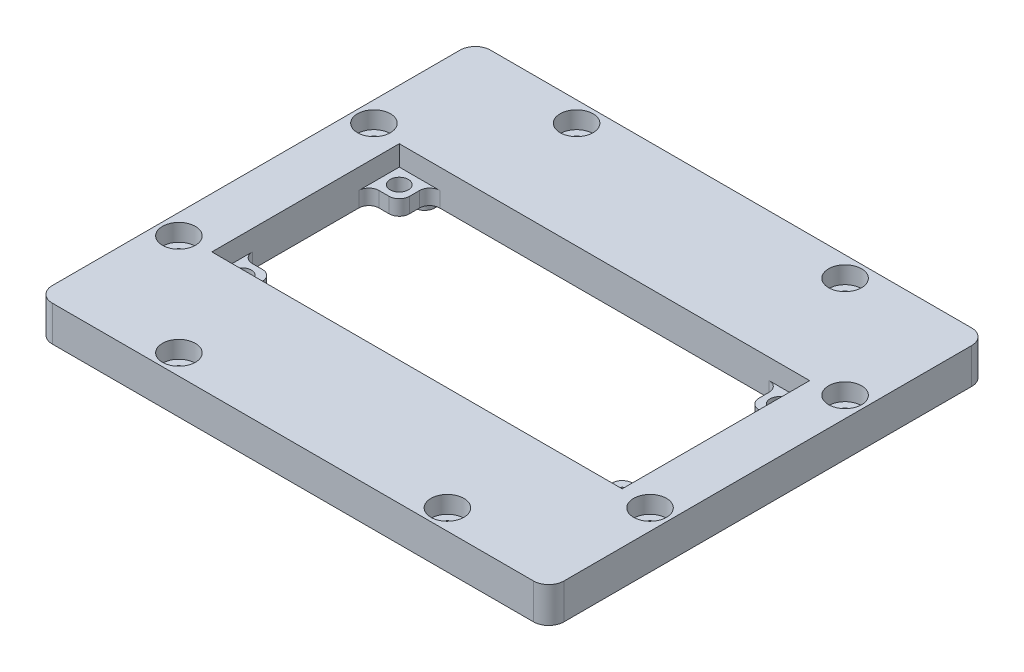
SolidWorks part; units mm, degrees
ref_plane "Front Plane" through (0, 0, 0) normal (0, 0, 1) x (1, 0, 0)
ref_plane "Top Plane" through (0, 0, 0) normal (0, 1, 0) x (1, 0, 0)
ref_plane "Right Plane" through (0, 0, 0) normal (1, 0, 0) x (0, 0, -1)
sketch "Sketch1" plane through (0, 0, 0) normal (0, 1, 0) x (1, 0, 0)
  line L1 (-50.5, -43.25) -> (50.5, -43.25)
  line L2 (-50.5, -43.25) -> (-50.5, 43.25)
  line L3 (-50.5, 43.25) -> (50.5, 43.25)
  line L4 (50.5, -43.25) -> (50.5, 43.25)
  line L5 (-50.5, -43.25) -> (50.5, 43.25) construction
  line L6 (-50.5, 43.25) -> (50.5, -43.25) construction
  point P0 (0, 0)
  dimension "D1" = 86.5
  dimension "D2" = 101
extrude "Boss-Extrude1" add sketch "Sketch1" along normal blind 7
sketch "Sketch2" plane through (0, 7, 0) normal (0, 1, 0) x (1, 0, 0)
  line L0 (50.5, -43.25) -> (50.5, 43.25) construction
  line L5 (-46.5, 39.25) -> (46.5, 39.25) construction
  line L6 (-46.5, 39.25) -> (-46.5, -39.25) construction
  line L11 (-46.5, -39.25) -> (46.5, -39.25) construction
  line L12 (46.5, 39.25) -> (46.5, -39.25) construction
  line L13 (0, -39.25) -> (0, 39.25) construction
  line L14 (-46.5, 0) -> (46.5, 0) construction
  line L15 (50.5, 43.25) -> (-50.5, 43.25) construction
  circle A0 centre (26.5, 39.25) radius 1
  circle A1 centre (46.5, 19.25) radius 1
  circle A2 centre (46.5, -19.25) radius 1
  circle A3 centre (26.5, -39.25) radius 1
  circle A4 centre (-26.5, -39.25) radius 1
  circle A5 centre (-46.5, -19.25) radius 1
  circle A6 centre (-46.5, 19.25) radius 1
  circle A7 centre (-26.5, 39.25) radius 1
  point P0 (0, 0)
  dimension "D1" = 2
  dimension "D2" = 20
  dimension "D3" = 20
  dimension "D4" = 4
  dimension "D5" = 4
hole_wizard "CBORE for M3 Hex Socket Head Cap Screw1" positions "Sketch5" profile "Sketch7" counterbore size "M3" standard "ISO" end condition through all
sketch "Sketch5" plane through (0, 7, 0) normal (0, 1, 0) x (1, 0, 0)
  point P19 (26.5, 39.25)
  point P22 (46.5, 19.25)
  point P25 (46.5, -19.25)
  point P28 (26.5, -39.25)
  point P31 (-26.5, -39.25)
  point P34 (-46.5, -19.25)
  point P37 (-46.5, 19.25)
  point P40 (-26.5, 39.25)
sketch "Sketch7" plane through (26.5, 7, -39.25) normal (1, 0, 0) x (0, 0, 1)
  line L0 (0, 0) -> (0, 7)
  line L1 (0, 7) -> (1.7, 7)
  line L3 (1.7, 7) -> (1.7, 3.4)
  line L4 (1.7, 3.4) -> (3.25, 3.4)
  line L5 (3.25, 3.4) -> (3.25, 0)
  line L7 (3.25, 0) -> (0, 0)
  line L11 (0, -6.35) -> (0, 107.95) construction
  dimension "Thru Hole Dia." = 3.4
  dimension "Thru Hole Depth" = 7
  dimension "C'Bore Dia." = 6.5
  dimension "C'Bore Depth" = 3.4
sketch "Sketch8" plane through (0, 0, 0) normal (0, -1, 0) x (1, 0, 0)
  line L0 (42, -34.75) -> (-42, -34.75) construction
  line L1 (42, -34.75) -> (27, -34.75)
  line L2 (27, -34.75) -> (27, -29.75)
  line L3 (27, -29.75) -> (37, -29.75)
  line L4 (37, -29.75) -> (37, -19.75)
  line L5 (37, -19.75) -> (42, -19.75)
  line L6 (42, -19.75) -> (42, -34.75)
  line L7 (-42, -19.75) -> (-42, -34.75)
  line L8 (-42, 34.75) -> (-27, 34.75)
  line L9 (-27, 34.75) -> (-27, 29.75)
  line L10 (-27, 29.75) -> (-37, 29.75)
  line L11 (-37, 29.75) -> (-37, 19.75)
  line L12 (42, -34.75) -> (42, 34.75)
  line L13 (42, 34.75) -> (-42, 34.75)
  line L14 (-42, 34.75) -> (-42, -34.75)
  line L15 (-42, -34.75) -> (42, -34.75)
  line L16 (42, -34.75) -> (42, 34.75) construction
  line L17 (42, 34.75) -> (-42, 34.75) construction
  line L18 (-42, 34.75) -> (-42, -34.75) construction
  line L19 (-42, -34.75) -> (42, -34.75) construction
  line L20 (-37, 19.75) -> (-42, 19.75)
  line L21 (-42, 19.75) -> (-42, 34.75)
  line L22 (0, 10.1371) -> (0, 0) construction
  line L23 (0, 0) -> (11.6132, 0) construction
  line L24 (42, 19.75) -> (42, 34.75)
  line L25 (37, 19.75) -> (42, 19.75)
  line L26 (37, 29.75) -> (37, 19.75)
  line L27 (27, 29.75) -> (37, 29.75)
  line L28 (27, 34.75) -> (27, 29.75)
  line L29 (42, 34.75) -> (27, 34.75)
  line L30 (-37, -19.75) -> (-42, -19.75)
  line L31 (-37, -29.75) -> (-37, -19.75)
  line L32 (-27, -29.75) -> (-37, -29.75)
  line L33 (-27, -34.75) -> (-27, -29.75)
  line L34 (-42, -34.75) -> (-27, -34.75)
  dimension "D2" = 15
  dimension "D3" = 10
  dimension "D1" = 8.5
extrude "Boss-Extrude2" add sketch "Sketch8" along normal blind 4
fillet "Fillet1" radius 2 24 edges at (-27, -2, -29.75) (-37, -2, -29.75) (-37, -2, -19.75) (-42, -2, -19.75) (-42, -2, -34.75) (-27, -2, -34.75) (27, -2, 29.75) (37, -2, 29.75) (37, -2, 19.75) (42, -2, 19.75) (42, -2, 34.75) (27, -2, 34.75) (37, -2, -19.75) (37, -2, -29.75) (27, -2, -29.75) (27, -2, -34.75) (42, -2, -34.75) (42, -2, -19.75) (-27, -2, 29.75) (-27, -2, 34.75) (-42, -2, 34.75) (-37, -2, 19.75) (-37, -2, 29.75) (-42, -2, 19.75)
fillet "Fillet2" radius 3 4 edges at (50.5, 3.5, 43.25) (-50.5, 3.5, 43.25) (50.5, 3.5, -43.25) (-50.5, 3.5, -43.25)
sketch "Sketch11" plane through (0, 7, 0) normal (0, 1, 0) x (1, 0, 0)
  line L0 (47.5, 43.25) -> (-47.5, 43.25) construction
  line L1 (-40.5, 18.25) -> (40.5, 18.25)
  line L2 (-40.5, 18.25) -> (-40.5, -18.75)
  line L3 (-40.5, -18.75) -> (40.5, -18.75)
  line L4 (40.5, 18.25) -> (40.5, -18.75)
  line L5 (0, -18.75) -> (0, 18.25) construction
  line L6 (-40.5, -0.25) -> (40.5, -0.25) construction
  circle A1 centre (-37.5, 15.25) radius 1.8 construction
  circle A2 centre (37.5, 15.25) radius 1.8 construction
  circle A3 centre (37.5, -15.75) radius 1.8 construction
  circle A4 centre (-37.5, -15.75) radius 1.8 construction
  point P0 (0, -0.25)
  dimension "D4" = 75
  dimension "D5" = 31
  dimension "D6" = 3.6
  dimension "D1" = 25
  dimension "D2" = 81
  dimension "D3" = 37
extrude "Cut-Extrude2" cut sketch "Sketch11" against normal through all and the other way through all
sketch "Sketch16" plane through (0, 7, 0) normal (0, 1, 0) x (1, 0, 0)
  line L0 (-32.5, -24.25) -> (-12.5, -24.25) construction
  line L1 (-32.5, -22.75) -> (-12.5, -22.75)
  line L2 (-32.5, -25.75) -> (-12.5, -25.75)
  line L3 (40.5, -18.75) -> (-40.5, -18.75) construction
  line L4 (-40.5, -18.75) -> (-40.5, 18.25) construction
  arc A0 (-32.5, -22.75) -> (-32.5, -25.75) centre (-32.5, -24.25) ccw
  arc A1 (-12.5, -25.75) -> (-12.5, -22.75) centre (-12.5, -24.25) ccw
  point P2 (-22.5, -24.25)
  dimension "D1" = 20
  dimension "D2" = 3
  dimension "D3" = 4
  dimension "D4" = 8
sketch "Sketch13" plane through (0, 0, 0) normal (0, -1, 0) x (1, 0, 0)
  line L0 (0, 18.75) -> (0, -18.25) construction
  line L1 (-40.5, 0.25) -> (40.5, 0.25) construction
  line L2 (0, 18.75) -> (0, -18.25) construction
  line L3 (-40.5, 0.25) -> (40.5, 0.25) construction
  line L4 (-34.5, 18.75) -> (-34.5, 12.75)
  line L5 (-40.5, -18.25) -> (-34.5, -18.25)
  line L6 (-40.5, -18.25) -> (-40.5, -12.25)
  line L7 (-40.5, -12.25) -> (-34.5, -12.25)
  line L8 (-34.5, -18.25) -> (-34.5, -12.25)
  line L9 (-40.5, 12.75) -> (-34.5, 12.75)
  line L10 (-40.5, 18.75) -> (-40.5, 12.75)
  line L11 (-40.5, 18.75) -> (-34.5, 18.75)
  line L12 (40.5, 18.75) -> (34.5, 18.75)
  line L13 (40.5, 18.75) -> (40.5, 12.75)
  line L14 (40.5, 12.75) -> (34.5, 12.75)
  line L15 (34.5, 18.75) -> (34.5, 12.75)
  line L16 (34.5, -18.25) -> (34.5, -12.25)
  line L17 (40.5, -12.25) -> (34.5, -12.25)
  line L18 (40.5, -18.25) -> (40.5, -12.25)
  line L19 (40.5, -18.25) -> (34.5, -18.25)
  circle A0 centre (-37.5, -15.25) radius 1.8 construction
  circle A1 centre (-37.5, -15.25) radius 1.8
  circle A2 centre (-37.5, 15.75) radius 1.8
  circle A3 centre (37.5, 15.75) radius 1.8
  circle A4 centre (37.5, -15.25) radius 1.8
  dimension "D1" = 3
extrude "Boss-Extrude3" add sketch "Sketch13" against normal blind 3
fillet "Fillet3" radius 2 12 edges at (34.5, 1.5, -12.25) (34.5, 1.5, 12.75) (-34.5, 1.5, -12.25) (-34.5, 1.5, 12.75) (40.5, 1.5, 12.75) (34.5, 1.5, 18.75) (-34.5, 1.5, 18.75) (-40.5, 1.5, 12.75) (-40.5, 1.5, -12.25) (-34.5, 1.5, -18.25) (40.5, 1.5, -12.25) (34.5, 1.5, -18.25)
